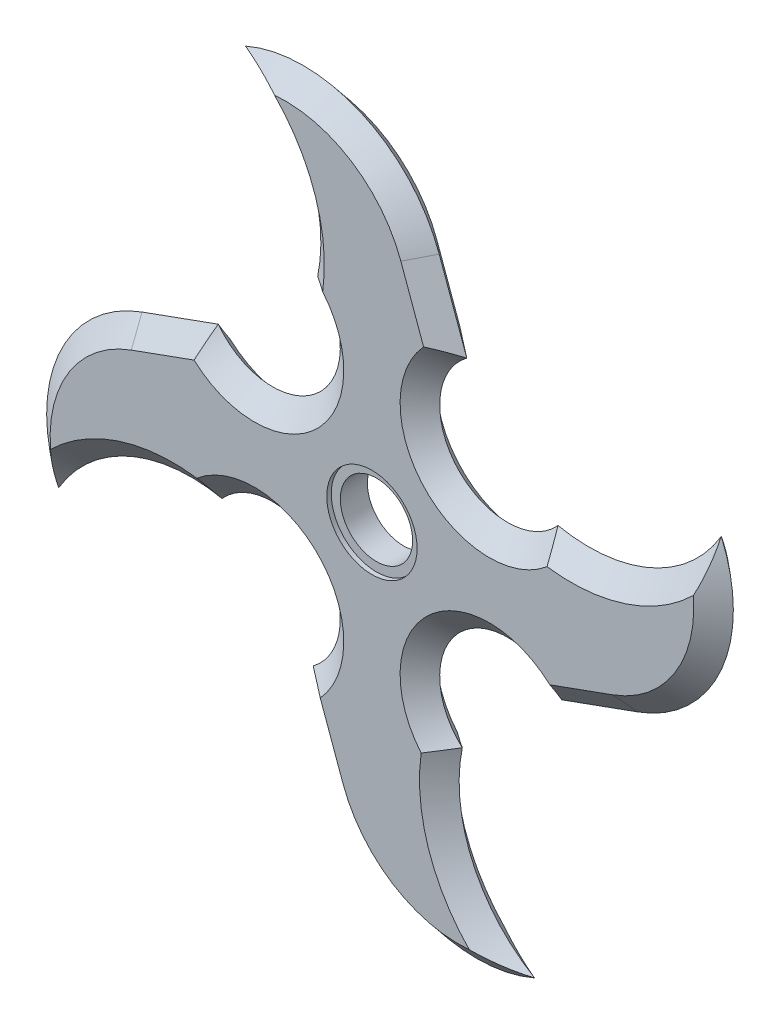
SolidWorks part; units mm, degrees
ref_plane "Front Plane" through (0, 0, 0) normal (0, 0, 1) x (1, 0, 0)
ref_plane "Top Plane" through (0, 0, 0) normal (0, 1, 0) x (1, 0, 0)
ref_plane "Right Plane" through (0, 0, 0) normal (1, 0, 0) x (0, 0, -1)
sketch "Sketch1" plane through (0, 0, 0) normal (0, 0, 1) x (1, 0, 0)
  line L0 (-40, 0) -> (40, 0) construction
  line L1 (0, 40) -> (0, -40) construction
  line L2 (28.2843, 28.2843) -> (0, 0) construction
  line L3 (0, 0) -> (28.2843, -28.2843) construction
  line L4 (27.4413, -5.445) -> (19, -8.5)
  line L5 (-5.445, -27.4413) -> (-8.5, -19)
  line L6 (-27.4413, 5.445) -> (-19, 8.5)
  line L7 (5.445, 27.4413) -> (8.5, 19)
  circle A0 centre (0, 0) radius 40
  arc A1 (36.6606, 16) -> (18.5902, 8) centre (22.0254, 24.6493) cw
  arc A2 (18.5902, 8) -> (7.6967, 7.6967) centre (13, 13) cw
  arc A3 (36.6606, 16) -> (27.4413, -5.445) centre (21.9964, 9.6) cw
  arc A4 (19, -8.5) -> (7.6967, -7.6967) centre (13, -13) ccw
  arc A5 (8, -18.5902) -> (7.6967, -7.6967) centre (13, -13) cw
  arc A6 (16, -36.6606) -> (8, -18.5902) centre (24.6493, -22.0254) cw
  arc A7 (16, -36.6606) -> (-5.445, -27.4413) centre (9.6, -21.9964) cw
  arc A8 (-8.5, -19) -> (-7.6967, -7.6967) centre (-13, -13) ccw
  arc A9 (-18.5902, -8) -> (-7.6967, -7.6967) centre (-13, -13) cw
  arc A10 (-36.6606, -16) -> (-18.5902, -8) centre (-22.0254, -24.6493) cw
  arc A11 (-36.6606, -16) -> (-27.4413, 5.445) centre (-21.9964, -9.6) cw
  arc A12 (-19, 8.5) -> (-7.6967, 7.6967) centre (-13, 13) ccw
  arc A13 (-8, 18.5902) -> (-7.6967, 7.6967) centre (-13, 13) cw
  arc A14 (-16, 36.6606) -> (-8, 18.5902) centre (-24.6493, 22.0254) cw
  arc A15 (-16, 36.6606) -> (5.445, 27.4413) centre (-9.6, 21.9964) cw
  arc A16 (8.5, 19) -> (7.6967, 7.6967) centre (13, 13) ccw
  point P52 (0, 0)
  dimension "D1" = 80
  dimension "D4" = 7.5
  dimension "D9" = 7.5
  dimension "D12" = 17
  dimension "D14" = 16
  dimension "D2" = 45
  dimension "D3" = 45
  dimension "D5" = 13
  dimension "D6" = 13
  dimension "D7" = 8
  dimension "D8" = 8.5
  dimension "D10" = 13
  dimension "D11" = 13
  dimension "D13" = 16
  dimension "D15" = 4
extrude "Boss-Extrude1" add sketch "Sketch1" along normal blind 2 draft 50 contours A16 L7 A15 A14 A13 A12 L6 A11 A10 A9 A8 L5 A7 A6 A5 A4 L4 A3 A1 A2
sketch "Sketch2" plane through (0, 0, 2) normal (0, 0, 1) x (1, 0, 0)
  circle A0 centre (0, 0) radius 5
  dimension "D1" = 10
extrude "Cut-Extrude1" cut sketch "Sketch2" against normal blind 0.5
sketch "Sketch4" plane through (0, 0, 2) normal (0, 0, 1) x (1, 0, 0)
  circle A0 centre (0, 0) radius 4
  dimension "D1" = 8
extrude "Cut-Extrude2" cut sketch "Sketch4" against normal through all
mirror "Mirror4" of "Cut-Extrude1", "Cut-Extrude2", "Boss-Extrude1"
